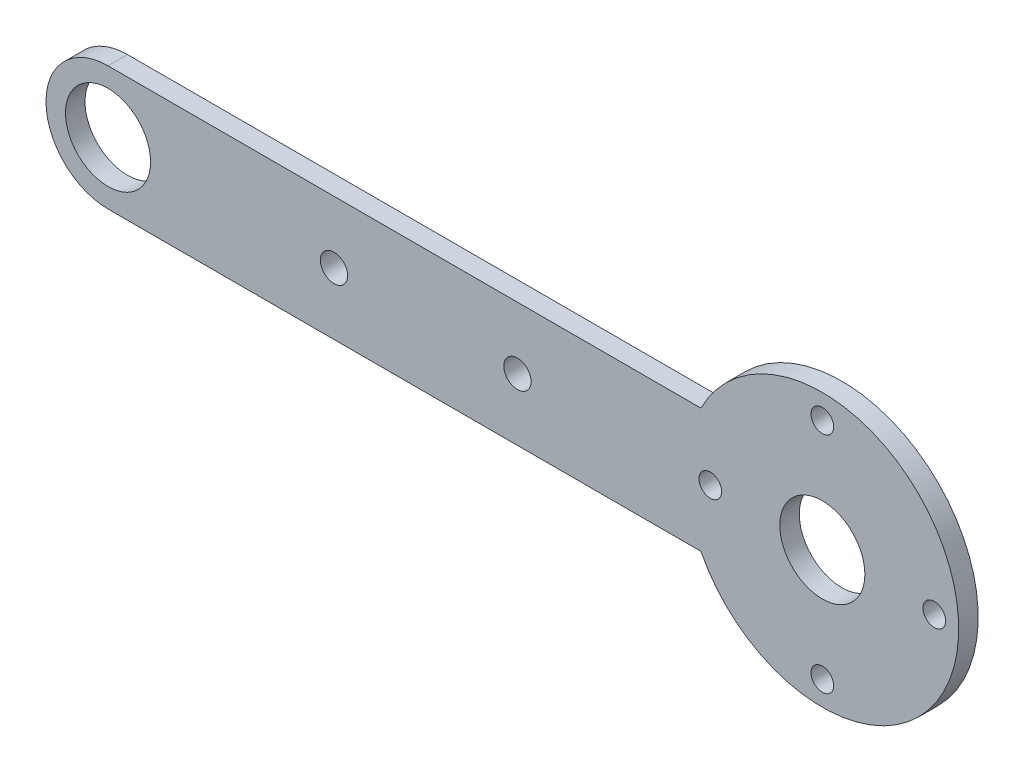
SolidWorks part; units mm, degrees
ref_plane "Plan de face" through (0, 0, 0) normal (0, 0, 1) x (1, 0, 0)
ref_plane "Plan de dessus" through (0, 0, 0) normal (0, 1, 0) x (1, 0, 0)
ref_plane "Plan de droite" through (0, 0, 0) normal (1, 0, 0) x (0, 0, -1)
sketch "Esquisse1" plane through (0, 0, 0) normal (0, 0, 1) x (1, 0, 0)
  line L0 (-110, 9.55) -> (-18.7029, 9.55)
  line L1 (-110, -9.55) -> (-18.7029, -9.55)
  line L2 (-110, 6.55) -> (-110, 9.55) construction
  line L3 (-103.45, 0) -> (-75.201, 0) construction
  line L4 (-75.201, 0) -> (-46.9519, 0) construction
  line L5 (-46.9519, 0) -> (-18.7029, 0) construction
  line L6 (-17.25, 0) -> (0, -17.25) construction
  line L7 (0, -17.25) -> (17.25, 0) construction
  line L8 (17.25, 0) -> (0, 17.25) construction
  line L9 (0, 17.25) -> (-17.25, 0) construction
  line L10 (19, 0) -> (21, 0) construction
  line L11 (0, 19) -> (0, 21) construction
  arc A0 (-18.7029, -9.55) -> (-18.7029, 9.55) centre (0, 0) ccw
  arc A1 (-110, 9.55) -> (-110, -9.55) centre (-110, 0) ccw
  circle A2 centre (-110, 0) radius 6.55
  circle A3 centre (0, 0) radius 6.55
  circle A4 centre (-75.201, 0) radius 2.1
  circle A5 centre (-46.9519, 0) radius 2.1
  circle A6 centre (-17.25, 0) radius 1.75
  circle A7 centre (0, 17.25) radius 1.75
  circle A8 centre (17.25, 0) radius 1.75
  circle A9 centre (0, -17.25) radius 1.75
  dimension "D1" = 42
  dimension "D2" = 13.1
  dimension "D5" = 4.2
  dimension "D6" = 3.5
  dimension "D3" = 3
  dimension "D4" = 110
  dimension "D7" = 17.25
extrude "Boss.-Extru.1" add sketch "Esquisse1" along normal blind 3
